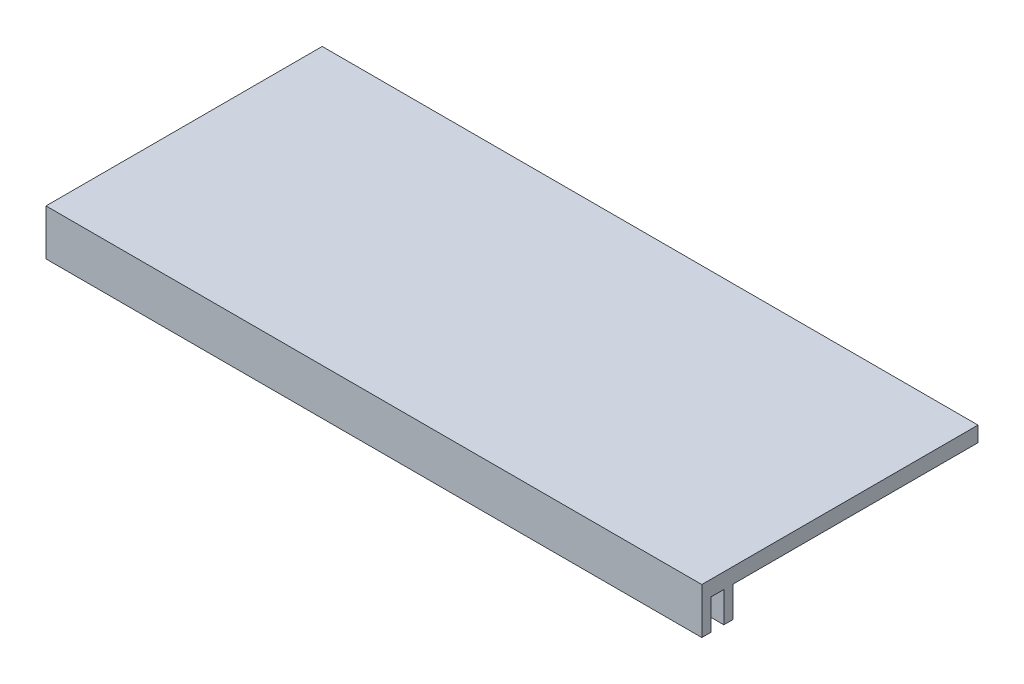
SolidWorks part; units mm, degrees
ref_plane "Front Plane" through (0, 0, 0) normal (0, 0, 1) x (1, 0, 0)
ref_plane "Top Plane" through (0, 0, 0) normal (0, 1, 0) x (1, 0, 0)
ref_plane "Right Plane" through (0, 0, 0) normal (1, 0, 0) x (0, 0, -1)
sketch "Sketch1" plane through (0, 0, 0) normal (0, 1, 0) x (1, 0, 0)
  line L1 (0, 0) -> (20, 0)
  line L2 (0, 0) -> (0, 80)
  line L3 (0, 80) -> (20, 80)
  line L4 (20, 0) -> (20, 80)
  dimension "D1" = 80
  dimension "D2" = 20
extrude "Boss-Extrude1" add sketch "Sketch1" along normal blind 5
sketch "Sketch2" plane through (0, 0, 0) normal (0, -1, 0) x (1, 0, 0)
  line L1 (20, 0) -> (0, 0)
  line L2 (20, 0) -> (20, 10.2)
  line L3 (20, 10.2) -> (0, 10.2)
  line L4 (0, 0) -> (0, 10.2)
  line L5 (0, -80) -> (0, 0) construction
  dimension "D1" = 10.2
  dimension "D2" = 0
extrude "Boss-Extrude2" add sketch "Sketch2" along normal blind 10 and the other way blind 5
sketch "Sketch3" plane through (0, -10, 0) normal (0, -1, 0) x (1, 0, 0)
  line L0 (20, 0) -> (20, 10.2) construction
  line L1 (20, 7.2) -> (0, 7.2)
  line L2 (20, 7.2) -> (20, 3)
  line L3 (20, 3) -> (0, 3)
  line L4 (0, 7.2) -> (0, 3)
  line L5 (0, 10.2) -> (0, 0) construction
  line L6 (0, 0) -> (20, 0) construction
  dimension "D1" = 4.2
  dimension "D2" = 3
extrude "Cut-Extrude1" cut sketch "Sketch3" against normal blind 10
sketch "Sketch5" plane through (0, 0, 0) normal (-1, 0, 0) x (0, 0, 1)
  line L0 (-80, 5) -> (10.2, 5) construction
  line L1 (10.2, -10) -> (7.2, -10)
  line L2 (10.2, -10) -> (10.2, 5)
  line L3 (10.2, 5) -> (7.2, 5)
  line L4 (7.2, -10) -> (7.2, 5)
  line L5 (7.2, 0) -> (7.2, -10) construction
  line M5 (0, -10) -> (3, -10)
  line M6 (3, -10) -> (3, 0)
  line M7 (3, 0) -> (7.2, 0)
  line M8 (7.2, 0) -> (7.2, -10)
  line M9 (7.2, -10) -> (10.2, -10)
  line M10 (10.2, -10) -> (10.2, 5)
  line M11 (10.2, 5) -> (-80, 5)
  line M12 (-80, 5) -> (-80, 0)
  line M13 (-80, 0) -> (0, 0)
  line M14 (0, 0) -> (0, -10)
extrude "Boss-Extrude3" add sketch "Sketch5" along normal blind 194.1589 contours L4 M7 M11 M12 M13 M14 M5 M6 | L4 M8 M9 M10 M11
